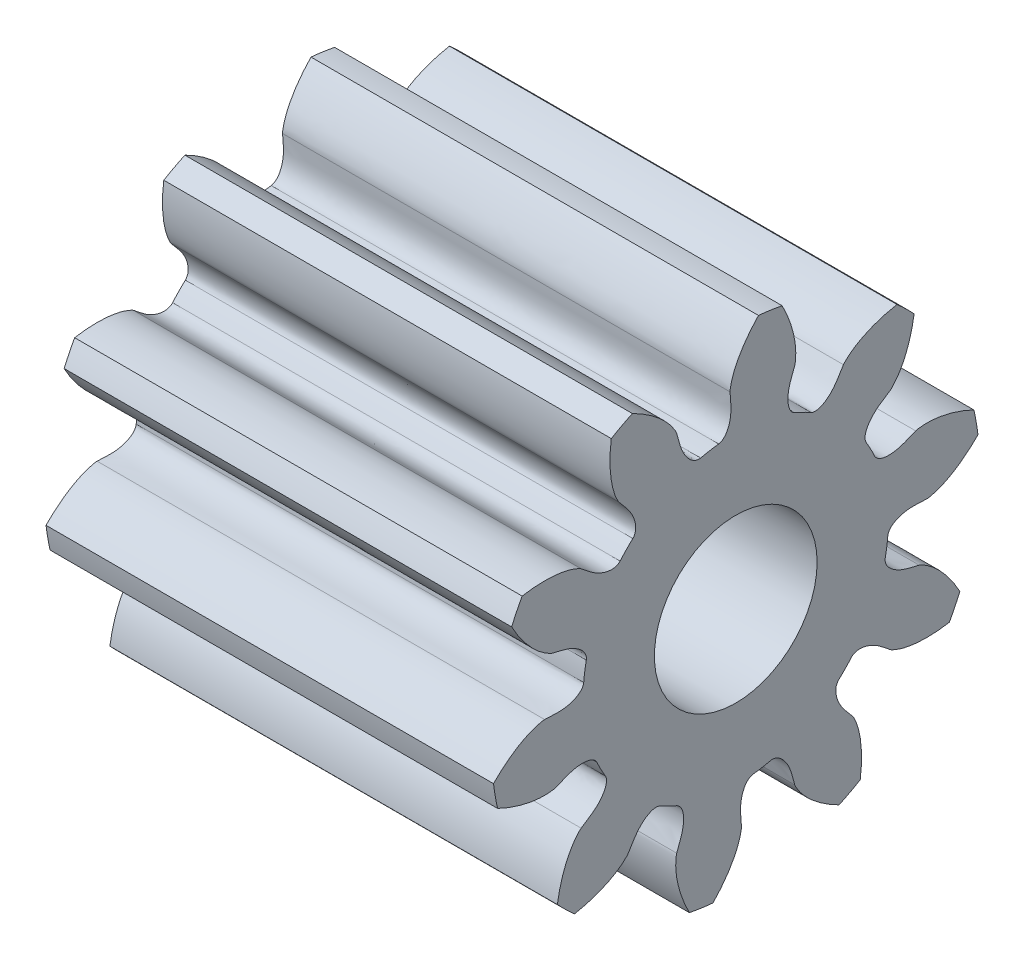
SolidWorks part; units mm, degrees
ref_plane "Plan de face" through (0, 0, 0) normal (0, 0, 1) x (1, 0, 0)
ref_plane "Plan de dessus" through (0, 0, 0) normal (0, 1, 0) x (1, 0, 0)
ref_plane "Plan de droite" through (0, 0, 0) normal (1, 0, 0) x (0, 0, -1)
sketch "Esquisse1" plane through (0, 0, 0) normal (1, 0, 0) x (0, 0, -1)
  arc A0 (2.9773, 0.3683) -> (2.9271, 0.6573) centre (0, 0) ccw
  arc A1 (2.1922, 2.048) -> (1.9817, 2.2523) centre (0, 0) ccw
  arc A2 (0.5698, 2.9454) -> (0.2794, 2.987) centre (0, 0) ccw
  arc A3 (-1.2703, 2.7178) -> (-1.5297, 2.5807) centre (0, 0) ccw
  arc A4 (-2.6252, 1.4521) -> (-2.7544, 1.1887) centre (0, 0) ccw
  arc A5 (-2.9773, -0.3683) -> (-2.9271, -0.6573) centre (0, 0) ccw
  arc A6 (-2.1922, -2.048) -> (-1.9817, -2.2523) centre (0, 0) ccw
  arc A7 (-0.5698, -2.9454) -> (-0.2794, -2.987) centre (0, 0) ccw
  arc A8 (1.2703, -2.7178) -> (1.5297, -2.5807) centre (0, 0) ccw
  arc A9 (2.6252, -1.4521) -> (2.7544, -1.1887) centre (0, 0) ccw
  arc A10 (1.8368, -0.3764) -> (1.8687, -0.154) centre (0, 0) ccw
  arc A11 (1.7073, 0.7751) -> (1.6023, 0.9738) centre (0, 0) ccw
  arc A12 (0.9256, 1.6306) -> (0.7239, 1.7296) centre (0, 0) ccw
  arc A13 (-0.2096, 1.8632) -> (-0.431, 1.8248) centre (0, 0) ccw
  arc A14 (-1.2648, 1.3842) -> (-1.4213, 1.2229) centre (0, 0) ccw
  arc A15 (-1.8368, 0.3764) -> (-1.8687, 0.154) centre (0, 0) ccw
  arc A16 (-1.7073, -0.7751) -> (-1.6023, -0.9738) centre (0, 0) ccw
  arc A17 (-0.9256, -1.6306) -> (-0.7239, -1.7296) centre (0, 0) ccw
  arc A18 (0.2096, -1.8632) -> (0.431, -1.8248) centre (0, 0) ccw
  arc A19 (1.2648, -1.3842) -> (1.4213, -1.2229) centre (0, 0) ccw
  circle A20 centre (0, 0) radius 1
  spline S0 degree 3 poles (2.349, 0) (2.3611, 0) (2.4126, 0.0085) (2.4945, 0.0326) (2.6584, 0.1065) (2.823, 0.2207) (2.9394, 0.3292) (2.9773, 0.3683) knots 0 0 0 0 0.036251 0.155621 0.255291 0.575255 0.744085 0.744085 0.744085 0.744085
  spline S1 degree 3 poles (2.2114, 0.7921) (2.2228, 0.7962) (2.2741, 0.8056) (2.3594, 0.8105) (2.5386, 0.7962) (2.7321, 0.7442) (2.8782, 0.6813) (2.9271, 0.6573) knots 0 0 0 0 0.036251 0.155621 0.255291 0.575255 0.744085 0.744085 0.744085 0.744085
  spline S2 degree 3 poles (1.9004, 1.3807) (1.9102, 1.3878) (1.9469, 1.4249) (1.9989, 1.4926) (2.0881, 1.6487) (2.1541, 1.8379) (2.1845, 1.9941) (2.1922, 2.048) knots 0 0 0 0 0.036251 0.155621 0.255291 0.575255 0.744085 0.744085 0.744085 0.744085
  spline S3 degree 3 poles (1.3235, 1.9407) (1.3303, 1.9507) (1.3663, 1.9885) (1.4324, 2.0425) (1.5858, 2.1363) (1.7728, 2.2079) (1.9281, 2.243) (1.9817, 2.2523) knots 0 0 0 0 0.036251 0.155621 0.255291 0.575255 0.744085 0.744085 0.744085 0.744085
  spline S4 degree 3 poles (0.7259, 2.234) (0.7296, 2.2455) (0.7375, 2.2971) (0.7398, 2.3825) (0.7202, 2.5612) (0.6625, 2.753) (0.5952, 2.8973) (0.5698, 2.9454) knots 0 0 0 0 0.036251 0.155621 0.255291 0.575255 0.744085 0.744085 0.744085 0.744085
  spline S5 degree 3 poles (-0.07, 2.348) (-0.0704, 2.36) (-0.0634, 2.4118) (-0.0417, 2.4943) (0.0272, 2.6604) (0.1365, 2.8283) (0.2415, 2.9479) (0.2794, 2.987) knots 0 0 0 0 0.036251 0.155621 0.255291 0.575255 0.744085 0.744085 0.744085 0.744085
  spline S6 degree 3 poles (-0.7259, 2.234) (-0.7296, 2.2455) (-0.7536, 2.2919) (-0.8019, 2.3623) (-0.9228, 2.4954) (-1.0823, 2.6166) (-1.2215, 2.6938) (-1.2703, 2.7178) knots 0 0 0 0 0.036251 0.155621 0.255291 0.575255 0.744085 0.744085 0.744085 0.744085
  spline S7 degree 3 poles (-1.4367, 1.8584) (-1.4441, 1.8679) (-1.4689, 1.9139) (-1.4999, 1.9934) (-1.5417, 2.1683) (-1.552, 2.3684) (-1.5374, 2.5268) (-1.5297, 2.5807) knots 0 0 0 0 0.036251 0.155621 0.255291 0.575255 0.744085 0.744085 0.744085 0.744085
  spline S8 degree 3 poles (-1.9004, 1.3807) (-1.9102, 1.3878) (-1.9568, 1.4112) (-2.0373, 1.4398) (-2.2133, 1.4764) (-2.4136, 1.4808) (-2.5715, 1.4614) (-2.6252, 1.4521) knots 0 0 0 0 0.036251 0.155621 0.255291 0.575255 0.744085 0.744085 0.744085 0.744085
  spline S9 degree 3 poles (-2.2547, 0.659) (-2.2663, 0.6624) (-2.3133, 0.6849) (-2.3852, 0.7311) (-2.5218, 0.848) (-2.6477, 1.0038) (-2.729, 1.1406) (-2.7544, 1.1887) knots 0 0 0 0 0.036251 0.155621 0.255291 0.575255 0.744085 0.744085 0.744085 0.744085
  spline S10 degree 3 poles (-2.349, 0) (-2.3611, 0) (-2.4126, -0.0085) (-2.4945, -0.0326) (-2.6584, -0.1065) (-2.823, -0.2207) (-2.9394, -0.3292) (-2.9773, -0.3683) knots 0 0 0 0 0.036251 0.155621 0.255291 0.575255 0.744085 0.744085 0.744085 0.744085
  spline S11 degree 3 poles (-2.2114, -0.7921) (-2.2228, -0.7962) (-2.2741, -0.8056) (-2.3594, -0.8105) (-2.5386, -0.7962) (-2.7321, -0.7442) (-2.8782, -0.6813) (-2.9271, -0.6573) knots 0 0 0 0 0.036251 0.155621 0.255291 0.575255 0.744085 0.744085 0.744085 0.744085
  spline S12 degree 3 poles (-1.9004, -1.3807) (-1.9102, -1.3878) (-1.9469, -1.4249) (-1.9989, -1.4926) (-2.0881, -1.6487) (-2.1541, -1.8379) (-2.1845, -1.9941) (-2.1922, -2.048) knots 0 0 0 0 0.036251 0.155621 0.255291 0.575255 0.744085 0.744085 0.744085 0.744085
  spline S13 degree 3 poles (-1.3235, -1.9407) (-1.3303, -1.9507) (-1.3663, -1.9885) (-1.4324, -2.0425) (-1.5858, -2.1363) (-1.7728, -2.2079) (-1.9281, -2.243) (-1.9817, -2.2523) knots 0 0 0 0 0.036251 0.155621 0.255291 0.575255 0.744085 0.744085 0.744085 0.744085
  spline S14 degree 3 poles (-0.7259, -2.234) (-0.7296, -2.2455) (-0.7375, -2.2971) (-0.7398, -2.3825) (-0.7202, -2.5612) (-0.6625, -2.753) (-0.5952, -2.8973) (-0.5698, -2.9454) knots 0 0 0 0 0.036251 0.155621 0.255291 0.575255 0.744085 0.744085 0.744085 0.744085
  spline S15 degree 3 poles (0.07, -2.348) (0.0704, -2.36) (0.0634, -2.4118) (0.0417, -2.4943) (-0.0272, -2.6604) (-0.1365, -2.8283) (-0.2415, -2.9479) (-0.2794, -2.987) knots 0 0 0 0 0.036251 0.155621 0.255291 0.575255 0.744085 0.744085 0.744085 0.744085
  spline S16 degree 3 poles (0.7259, -2.234) (0.7296, -2.2455) (0.7536, -2.2919) (0.8019, -2.3623) (0.9228, -2.4954) (1.0823, -2.6166) (1.2215, -2.6938) (1.2703, -2.7178) knots 0 0 0 0 0.036251 0.155621 0.255291 0.575255 0.744085 0.744085 0.744085 0.744085
  spline S17 degree 3 poles (1.4367, -1.8584) (1.4441, -1.8679) (1.4689, -1.9139) (1.4999, -1.9934) (1.5417, -2.1683) (1.552, -2.3684) (1.5374, -2.5268) (1.5297, -2.5807) knots 0 0 0 0 0.036251 0.155621 0.255291 0.575255 0.744085 0.744085 0.744085 0.744085
  spline S18 degree 3 poles (1.9004, -1.3807) (1.9102, -1.3878) (1.9568, -1.4112) (2.0373, -1.4398) (2.2133, -1.4764) (2.4136, -1.4808) (2.5715, -1.4614) (2.6252, -1.4521) knots 0 0 0 0 0.036251 0.155621 0.255291 0.575255 0.744085 0.744085 0.744085 0.744085
  spline S19 degree 3 poles (2.2547, -0.659) (2.2663, -0.6624) (2.3133, -0.6849) (2.3852, -0.7311) (2.5218, -0.848) (2.6477, -1.0038) (2.729, -1.1406) (2.7544, -1.1887) knots 0 0 0 0 0.036251 0.155621 0.255291 0.575255 0.744085 0.744085 0.744085 0.744085
  spline S20 degree 3 poles (2.349, 0) (2.2648, 0) (2.1034, 0.0291) (1.8817, -0.0633) (1.8687, -0.154) knots 0 0 0 0 0.252618 0.527509 0.527509 0.527509 0.527509
  spline S21 degree 3 poles (2.2547, -0.659) (2.1739, -0.6353) (2.0108, -0.618) (1.8238, -0.4671) (1.8368, -0.3764) knots 0 0 0 0 0.252618 0.527509 0.527509 0.527509 0.527509
  spline S22 degree 3 poles (1.9004, 1.3807) (1.8323, 1.3312) (1.6846, 1.2599) (1.5595, 1.0548) (1.6023, 0.9738) knots 0 0 0 0 0.252618 0.527509 0.527509 0.527509 0.527509
  spline S23 degree 3 poles (2.2114, 0.7921) (2.1321, 0.7637) (1.99, 0.682) (1.7501, 0.6941) (1.7073, 0.7751) knots 0 0 0 0 0.252618 0.527509 0.527509 0.527509 0.527509
  spline S24 degree 3 poles (0.7259, 2.234) (0.6999, 2.1539) (0.6223, 2.0095) (0.6416, 1.77) (0.7239, 1.7296) knots 0 0 0 0 0.252618 0.527509 0.527509 0.527509 0.527509
  spline S25 degree 3 poles (1.3235, 1.9407) (1.276, 1.8711) (1.2091, 1.7214) (1.0079, 1.5902) (0.9256, 1.6306) knots 0 0 0 0 0.252618 0.527509 0.527509 0.527509 0.527509
  spline S26 degree 3 poles (-0.7259, 2.234) (-0.6999, 2.1539) (-0.6776, 1.9915) (-0.5213, 1.8091) (-0.431, 1.8248) knots 0 0 0 0 0.252618 0.527509 0.527509 0.527509 0.527509
  spline S27 degree 3 poles (-0.07, 2.348) (-0.0675, 2.2638) (-0.0336, 2.1034) (-0.1193, 1.8789) (-0.2096, 1.8632) knots 0 0 0 0 0.252618 0.527509 0.527509 0.527509 0.527509
  spline S28 degree 3 poles (-1.9004, 1.3807) (-1.8323, 1.3312) (-1.7188, 1.2128) (-1.4851, 1.1572) (-1.4213, 1.2229) knots 0 0 0 0 0.252618 0.527509 0.527509 0.527509 0.527509
  spline S29 degree 3 poles (-1.4367, 1.8584) (-1.3852, 1.7918) (-1.2635, 1.6819) (-1.2009, 1.4499) (-1.2648, 1.3842) knots 0 0 0 0 0.252618 0.527509 0.527509 0.527509 0.527509
  spline S30 degree 3 poles (-2.349, 0) (-2.2648, 0) (-2.1034, -0.0291) (-1.8817, 0.0633) (-1.8687, 0.154) knots 0 0 0 0 0.252618 0.527509 0.527509 0.527509 0.527509
  spline S31 degree 3 poles (-2.2547, 0.659) (-2.1739, 0.6353) (-2.0108, 0.618) (-1.8238, 0.4671) (-1.8368, 0.3764) knots 0 0 0 0 0.252618 0.527509 0.527509 0.527509 0.527509
  spline S32 degree 3 poles (-1.9004, -1.3807) (-1.8323, -1.3312) (-1.6846, -1.2599) (-1.5595, -1.0548) (-1.6023, -0.9738) knots 0 0 0 0 0.252618 0.527509 0.527509 0.527509 0.527509
  spline S33 degree 3 poles (-2.2114, -0.7921) (-2.1321, -0.7637) (-1.99, -0.682) (-1.7501, -0.6941) (-1.7073, -0.7751) knots 0 0 0 0 0.252618 0.527509 0.527509 0.527509 0.527509
  spline S34 degree 3 poles (-0.7259, -2.234) (-0.6999, -2.1539) (-0.6223, -2.0095) (-0.6416, -1.77) (-0.7239, -1.7296) knots 0 0 0 0 0.252618 0.527509 0.527509 0.527509 0.527509
  spline S35 degree 3 poles (-1.3235, -1.9407) (-1.276, -1.8711) (-1.2091, -1.7214) (-1.0079, -1.5902) (-0.9256, -1.6306) knots 0 0 0 0 0.252618 0.527509 0.527509 0.527509 0.527509
  spline S36 degree 3 poles (0.7259, -2.234) (0.6999, -2.1539) (0.6776, -1.9915) (0.5213, -1.8091) (0.431, -1.8248) knots 0 0 0 0 0.252618 0.527509 0.527509 0.527509 0.527509
  spline S37 degree 3 poles (0.07, -2.348) (0.0675, -2.2638) (0.0336, -2.1034) (0.1193, -1.8789) (0.2096, -1.8632) knots 0 0 0 0 0.252618 0.527509 0.527509 0.527509 0.527509
  spline S38 degree 3 poles (1.9004, -1.3807) (1.8323, -1.3312) (1.7188, -1.2128) (1.4851, -1.1572) (1.4213, -1.2229) knots 0 0 0 0 0.252618 0.527509 0.527509 0.527509 0.527509
  spline S39 degree 3 poles (1.4367, -1.8584) (1.3852, -1.7918) (1.2635, -1.6819) (1.2009, -1.4499) (1.2648, -1.3842) knots 0 0 0 0 0.252618 0.527509 0.527509 0.527509 0.527509
  dimension "D1" = 2
extrude "Boss.-Extru.1" add sketch "Esquisse1" along normal blind 5.5
